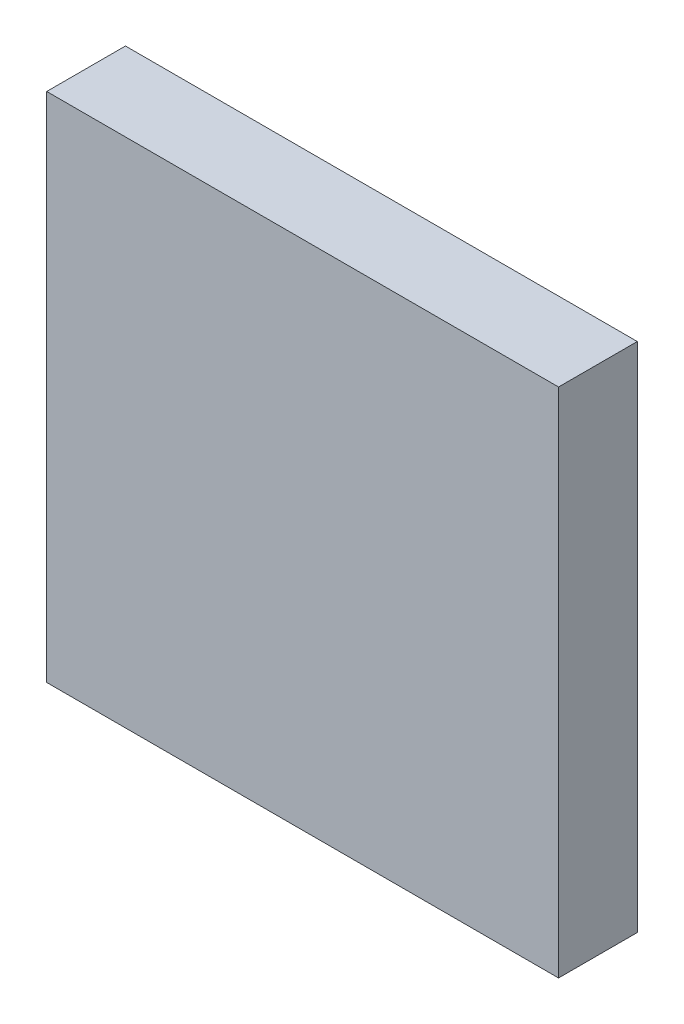
SolidWorks part; units mm, degrees
ref_plane "Plan de face" through (0, 0, 0) normal (0, 0, 1) x (1, 0, 0)
ref_plane "Plan de dessus" through (0, 0, 0) normal (0, 1, 0) x (1, 0, 0)
ref_plane "Plan de droite" through (0, 0, 0) normal (1, 0, 0) x (0, 0, -1)
sketch "Esquisse1" plane through (0, 0, 0) normal (0, 0, 1) x (1, 0, 0)
  line L1 (-41.275, 41.275) -> (41.275, 41.275)
  line L2 (-41.275, 41.275) -> (-41.275, -41.275)
  line L3 (-41.275, -41.275) -> (41.275, -41.275)
  line L4 (41.275, 41.275) -> (41.275, -41.275)
  line L5 (-41.275, 41.275) -> (41.275, -41.275) construction
  line L6 (-41.275, -41.275) -> (41.275, 41.275) construction
  point P0 (0, 0)
  dimension "D1" = 82.55
  dimension "D2" = 82.55
extrude "Boss.-Extru.1" add sketch "Esquisse1" along normal blind 12.7
